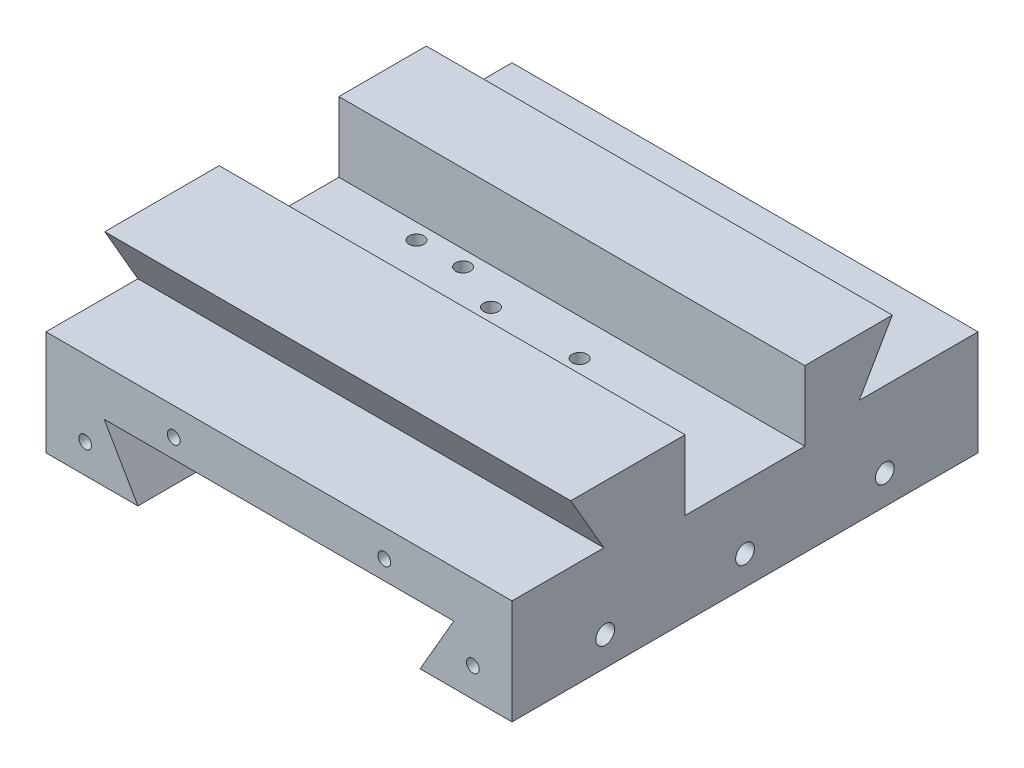
SolidWorks part; units mm, degrees
material "Ductile Iron"
ref_plane "Front Plane" through (0, 0, 0) normal (0, 0, 1) x (1, 0, 0)
ref_plane "Top Plane" through (0, 0, 0) normal (0, 1, 0) x (1, 0, 0)
ref_plane "Right Plane" through (0, 0, 0) normal (1, 0, 0) x (0, 0, -1)
sketch "Sketch10" plane through (0, 0, 0) normal (0, 0, 1) x (1, 0, 0)
  line B0 (-63.5, -15.875) -> (63.5, -15.875)
  line B1 (63.5, 0) -> (38.4596, 0)
  line B2 (38.4596, 0) -> (47.625, 15.875)
  line B3 (47.625, 15.875) -> (16.0563, 15.875)
  line B4 (-40.2927, 15.875) -> (-31.1272, 0)
  line B5 (-31.1272, 0) -> (-63.5, 0)
  line B6 (-63.5, 0) -> (-63.5, -15.875)
  line B7 (-38.4596, 0) -> (-47.625, 15.875)
  line B8 (-47.625, 15.875) -> (-40.2927, 15.875)
  line B9 (-16.0563, 15.875) -> (-16.0563, -3.175)
  line B10 (-16.0563, -3.175) -> (16.0563, -3.175)
  line B11 (16.0563, -3.175) -> (16.0563, 15.875)
  line B12 (-16.0563, 15.875) -> (-40.2927, 15.875)
  line B13 (-63.5, 0) -> (-63.5, 31.75)
  line B14 (-63.5, 31.75) -> (63.5, 31.75)
  line B15 (63.5, 31.75) -> (63.5, 0)
  line B16 (-16.0563, 15.875) -> (16.0563, 15.875)
  line B17 (0, 31.75) -> (0, -15.875) construction
  line B18 (-38.4596, 0) -> (38.4596, 0) construction
  line B19 (-28.702, 21.082) -> (28.702, 21.082) construction
  line B20 (-25.4, -8.001) -> (25.4, -8.001) construction
  line B21 (-25.4, -8.001) -> (-25.4, 7.9375) construction
  line B22 (25.4, -8.001) -> (25.4, 7.9375) construction
  line B23 (-52.832, 7.9375) -> (52.832, 7.9375) construction
  circle B24 centre (0, 6.35) radius 18.669 construction
  line B25 (40.2927, 15.875) -> (31.1272, 0)
  line B26 (31.1272, 0) -> (38.4596, 0)
sketch_block_instance "dovetail pair-1"
sketch_block "dovetail pair" parameters "D8"=37.338, "D1"=60, "D2"=127, "D3"=6.35, "D4"=15.875, "D5"=31.75, "D6"=95.25, "D7"=19.05, "D9"=60, "D10"=31.75, "D11"=50.8, "D12"=23.876, "D13"=7.874, "D14"=10.668, "D15"=34.798, "D16"=21.082, "D17"=7.9375
sketch "Sketch11"
sketch_block_instance "dovetail pair-3"
sketch "female-dovetail-profile" plane through (0, 0, 0) normal (0, 0, 1) x (1, 0, 0)
  line L0 (-47.625, 15.875) -> (-40.2927, 15.875) construction
  line L1 (-16.0563, 15.875) -> (-40.2927, 15.875) construction
  line L2 (-16.0563, 15.875) -> (16.0563, 15.875) construction
  line L3 (47.625, 15.875) -> (16.0563, 15.875) construction
  line L4 (-47.625, 15.875) -> (-40.2927, 15.875)
  line L5 (-16.0563, 15.875) -> (-40.2927, 15.875)
  line L6 (-16.0563, 15.875) -> (16.0563, 15.875)
  line L7 (47.625, 15.875) -> (16.0563, 15.875)
  line L8 (-38.4596, 0) -> (-47.625, 15.875) construction
  line L9 (-63.5, 0) -> (-63.5, 31.75) construction
  line L10 (63.5, 31.75) -> (63.5, 0) construction
  line L11 (63.5, 0) -> (38.4596, 0) construction
  line L12 (38.4596, 0) -> (47.625, 15.875) construction
  line L13 (-38.4596, 0) -> (-47.625, 15.875)
  line L14 (-63.5, 0) -> (-63.5, 31.75)
  line L15 (63.5, 31.75) -> (63.5, 0)
  line L16 (63.5, 0) -> (38.4596, 0)
  line L17 (38.4596, 0) -> (47.625, 15.875)
  line L18 (-38.4596, 0) -> (-63.5, 0)
  line L20 (63.5, 31.75) -> (63.5, 44.45)
  line L21 (63.5, 44.45) -> (-63.5, 44.45)
  line L22 (-63.5, 44.45) -> (-63.5, 31.75)
  dimension "D1" = 44.45
extrude "x-carriage-extrude" add sketch "female-dovetail-profile" along normal mid plane 127
sketch "male-dovetail-shoulder-profile" plane through (0, 0, 0) normal (1, 0, 0) x (0, 0, -1)
  line L0 (40.2927, 44.45) -> (31.1272, 28.575) construction
  line L1 (-40.2927, 44.45) -> (-31.1272, 28.575) construction
  line L2 (38.4596, 28.575) -> (47.625, 44.45) construction
  line L3 (63.5, 28.575) -> (38.4596, 28.575) construction
  line L4 (-38.4596, 28.575) -> (-47.625, 44.45) construction
  line L5 (-40.2927, 44.45) -> (-31.1272, 28.575) construction
  line L6 (38.4596, 28.575) -> (47.625, 44.45) construction
  line L7 (63.5, 28.575) -> (38.4596, 28.575)
  line L8 (-16.0563, 44.45) -> (-16.0563, 25.4) construction
  line L9 (-16.0563, 25.4) -> (16.0563, 25.4) construction
  line L10 (16.0563, 25.4) -> (16.0563, 44.45) construction
  line L11 (47.625, 44.45) -> (16.0563, 44.45) construction
  line L12 (-47.4784, 44.196) -> (-38.4596, 28.575)
  line L13 (-16.0563, 44.45) -> (-40.2927, 44.45) construction
  line L14 (-16.0563, 44.45) -> (-16.0563, 25.4) construction
  line L15 (-16.0563, 25.4) -> (16.0563, 25.4) construction
  line L16 (16.0563, 25.4) -> (16.0563, 44.45) construction
  line L17 (47.625, 44.45) -> (16.0563, 44.45) construction
  line L18 (-38.4596, 28.575) -> (-63.5, 28.575)
  line L19 (-16.0563, 44.45) -> (-40.2927, 44.45) construction
  line L20 (-47.4784, 44.196) -> (-16.3103, 44.196)
  line L21 (-16.3103, 44.196) -> (-16.3103, 25.146)
  line L22 (-16.3103, 25.146) -> (16.3103, 25.146)
  line L23 (16.3103, 25.146) -> (16.3103, 44.196)
  line L24 (16.3103, 44.196) -> (40.146, 44.196)
  line L25 (40.146, 44.196) -> (31.1272, 28.575)
  line L26 (-63.5, 28.575) -> (-63.5, 44.45)
  line L27 (-63.5, 44.45) -> (63.5, 44.45)
  line L28 (63.5, 44.45) -> (63.5, 28.575)
  line L29 (0, 60.325) -> (0, 12.7) construction
  line L30 (31.1272, 28.575) -> (38.4596, 28.575) construction
  line L31 (31.1272, 28.575) -> (38.4596, 28.575)
  point P16 (0, 25.146)
  dimension "D2" = 0.254
  dimension "D3" = 0.254
  dimension "D1" = 0.254
extrude "y-guide-cut-extrude" cut sketch "male-dovetail-shoulder-profile" against normal mid plane 127
hole_wizard "#8-32 Tapped Hole1" positions "Sketch4" profile "Sketch5" tap size "#8-32" standard "ANSI Inch"
sketch "Sketch4" plane through (0, -15.875, 63.5) normal (0, 0, 1) x (1, 0, 0)
  point P32 (-52.832, 23.8125)
  point P34 (-28.702, 36.957)
  point P36 (28.702, 36.957)
  point P38 (52.832, 23.8125)
cosmetic thread "Hole Thread12" parameters "D1"=8.382, "D2"=4.1656
sketch "Sketch5" plane through (-52.832, 7.9375, 63.5) normal (1, 0, 0) x (0, -1, 0)
  line L0 (0, 0) -> (0, 13.3822)
  line L1 (0, 13.3822) -> (1.7272, 12.3444)
  line L2 (1.7272, 12.3444) -> (1.7272, 0)
  line L3 (1.7272, 0) -> (0, 0)
  line L4 (0, 13.3822) -> (-1.7272, 12.3444) construction
  line L5 (0, -6.35) -> (0, 107.95) construction
  dimension "Tap Drill Dia." = 3.4544
  dimension "Tap Drill Depth" = 12.3444
  dimension "Drill Angle" = 118
cosmetic thread "Hole Thread20" parameters "D1"=8.382, "D2"=4.1656
cosmetic thread "Hole Thread21" parameters "D1"=8.382, "D2"=4.1656
cosmetic thread "Hole Thread22" parameters "D1"=8.382, "D2"=4.1656
hole_wizard "#8-32 Tapped Hole2" positions "Sketch6" profile "Sketch7" tap size "#8-32" standard "ANSI Inch"
sketch "Sketch6" plane through (0, -15.875, -63.5) normal (0, 0, -1) x (-1, 0, 0)
  point P8 (-52.832, 23.8125)
  point P10 (-28.702, 36.957)
  point P12 (28.702, 36.957)
  point P14 (52.832, 23.8125)
cosmetic thread "Hole Thread15" parameters "D1"=8.382, "D2"=4.1656
sketch "Sketch7" plane through (52.832, 7.9375, -63.5) normal (1, 0, 0) x (0, 1, 0)
  line L0 (0, 0) -> (0, 13.4838)
  line L1 (0, 13.4838) -> (1.7272, 12.446)
  line L2 (1.7272, 12.446) -> (1.7272, 0)
  line L5 (1.7272, 0) -> (0, 0)
  line L10 (0, 13.4838) -> (-1.7272, 12.446) construction
  line L11 (0, -6.35) -> (0, 107.95) construction
  dimension "Tap Drill Dia." = 3.4544
  dimension "Tap Drill Depth" = 12.446
  dimension "Drill Angle" = 118
cosmetic thread "Hole Thread23" parameters "D1"=8.382, "D2"=4.1656
cosmetic thread "Hole Thread24" parameters "D1"=8.382, "D2"=4.1656
cosmetic thread "Hole Thread25" parameters "D1"=8.382, "D2"=4.1656
hole_wizard "gib screw 1/4-20 Tapped Hole1" positions "Sketch9" profile "Sketch8" tap size "1/4-20" standard "ANSI Inch"
sketch "Sketch9" plane through (0, 0, 0) normal (1, 0, 0) x (0, 0, -1)
  line L2 (0, 15.875) -> (0, 0) construction
  line L4 (63.5, 7.9375) -> (-63.5, 7.9375) construction
  line L7 (-38.1, 7.9375) -> (0, 7.9375) construction
  line L8 (63.5, 0) -> (63.5, 28.575) construction
  line L9 (-63.5, 15.875) -> (63.5, 15.875) construction
  line L10 (-63.5, 15.875) -> (63.5, 15.875)
  point P0 (-38.1, 7.9375)
  point P16 (0, 7.9375)
  point P22 (0, 7.9375)
  point P23 (38.1, 7.9375)
  dimension "D1" = 38.1
  dimension "D2" = 3
sketch "Sketch8" plane through (0, 7.9375, 38.1) normal (0, 1, 0) x (0, 0, 1)
  line L0 (0, 0) -> (0, 63.5)
  line L1 (0, 63.5) -> (2.5527, 63.5)
  line L2 (2.5527, 63.5) -> (2.5527, 0)
  line L5 (2.5527, 0) -> (0, 0)
  line L11 (0, -6.35) -> (0, 107.95) construction
  dimension "Thru Tap Drill Dia." = 5.1054
  dimension "Thru Tap Drill Depth" = 63.5
cosmetic thread "Hole Thread36" parameters "D1"=23.2203, "D2"=6.35
cosmetic thread "Hole Thread37" parameters "D1"=23.2203, "D2"=6.35
cosmetic thread "Hole Thread38" parameters "D1"=23.2203, "D2"=6.35
hole_wizard "#10-32 Tapped Hole1" positions "Sketch13" profile "Sketch12" tap size "#10-32" standard "ANSI Inch"
sketch "Sketch13" plane through (0, 25.146, 0) normal (0, 1, 0) x (1, 0, 0)
  line L1 (-12.065, -6.35) -> (12.065, -6.35) construction
  line L2 (-12.065, -6.35) -> (-12.065, 6.35) construction
  line L3 (-12.065, 6.35) -> (12.065, 6.35) construction
  line L4 (12.065, -6.35) -> (12.065, 6.35) construction
  line L6 (-38.1, -12.065) -> (-25.4, -12.065) construction
  line L7 (-38.1, -12.065) -> (-38.1, 12.065) construction
  line L8 (-38.1, 12.065) -> (-25.4, 12.065) construction
  line L9 (-25.4, -12.065) -> (-25.4, 12.065) construction
  line L10 (0, 16.3103) -> (0, -16.3103) construction
  line L12 (-63.5, -16.3103) -> (63.5, -16.3103) construction
  line L13 (-63.5, 0) -> (63.5, 0) construction
  line L14 (-63.5, -16.3103) -> (-63.5, 16.3103) construction
  line L15 (63.5, -16.3103) -> (63.5, 16.3103) construction
  line L16 (-63.5, 16.3103) -> (63.5, 16.3103) construction
  point P0 (-38.1, 12.065)
  point P2 (-38.1, -12.065)
  point P4 (-12.065, 6.35)
  point P6 (-25.4, 12.065)
  point P8 (-25.4, -12.065)
  point P10 (12.065, 6.35)
  point P12 (12.065, -6.35)
  point P14 (-12.065, -6.35)
  point P155 (0, 0)
  point P157 (0, -6.35)
  point P158 (12.065, 0)
  point P159 (-25.4, 0)
  dimension "D1" = 24.13
  dimension "D2" = 24.13
  dimension "D3" = 12.7
  dimension "D4" = 12.7
  dimension "D5" = 38.1
sketch "Sketch12" plane through (-38.1, 25.146, -12.065) normal (1, 0, 0) x (0, 0, 1)
  line L0 (0, 0) -> (0, 9.271)
  line L1 (0, 9.271) -> (2.0193, 9.271)
  line L2 (2.0193, 9.271) -> (2.0193, 0)
  line L5 (2.0193, 0) -> (0, 0)
  line L11 (0, -6.35) -> (0, 107.95) construction
  dimension "Thru Tap Drill Dia." = 4.0386
  dimension "Thru Tap Drill Depth" = 9.271
cosmetic thread "Hole Thread28" parameters "D2"=4.826
cosmetic thread "Hole Thread29" parameters "D2"=4.826
cosmetic thread "Hole Thread30" parameters "D2"=4.826
cosmetic thread "Hole Thread31" parameters "D2"=4.826
cosmetic thread "Hole Thread32" parameters "D2"=4.826
cosmetic thread "Hole Thread33" parameters "D2"=4.826
cosmetic thread "Hole Thread34" parameters "D2"=4.826
cosmetic thread "Hole Thread35" parameters "D2"=4.826
equation "\"dovetail-angle\" = 60"
equation "\"dovetail-stock-width\" = 5"
equation "\"dovetail-stock-height\" = 1.25"
equation "\"dovetail-depth\" = 0.5 * \"dovetail-stock-height\""
equation "\"dovetail-throat-width\" = \"dovetail-stock-width\" - (2 * \"dovetail-depth\")"
equation "\"delta-x\" = 6"
equation "\"delta-y\" = 3"
equation "\"delta-z\"= 2.5"
equation "\"gib-thickness\" = 0.25"
equation "\"x-slide-length\" = \"dovetail-stock-width\" + \"delta-x\""
equation "\"y-slide-length\" = \"dovetail-stock-width\" + \"delta-y\""
equation "\"dog-point-diam\" = .149"
equation "\"D1@female-dovetail-profile\"=\"dovetail-double-height\""
equation "\"D1@x-carriage-extrude\"=\"dovetail-stock-width\""
equation "\"dog-point-length\" = .067"
equation "\"dovetail-double-height\" = 2 * \"dovetail-depth\" + 0.5"
equation "\"D2@male-dovetail-shoulder-profile\"=\"acme_nut_clearance\""
equation "\"D3@male-dovetail-shoulder-profile\"=\"dovetail_male_clearance\""
equation "\"acme-major-diam\" = .5"
equation "\"acme-pitch-diam\" = 0.45"
equation "\"acme-minor-diam\" = 0.4"
equation "\"acme-nut-od\" = 1.47"
equation "\"acme-nut-length\" = 1"
equation "\"acme-nut-trim-height\" = .75"
equation "\"screw-bearing-od\" = 0.5"
equation "\"screw-bearing-length\" = .375"
equation "\"screw-bearing-id\" = .375"
equation "\"end-plate-thickness\" = \"screw-bearing-length\""
equation "\"screw-add-length\" = 2 * \"end-plate-thickness\" + 1 + 0.5"
equation "\"x-screw-length\" = \"x-slide-length\" + \"screw-add-length\""
equation "\"y-screw-length\" = \"y-slide-length\" + \"screw-add-length\""
equation "\"acme-nut-mount-hole-space-horz\" = 0.95"
equation "\"acme-nut-mount-hole-space-vert\" = 0.5 * \"acme-nut-length\""
equation "\"D2@dovetail pair\"=\"dovetail-stock-width\""
equation "\"D1@dovetail pair\"=\"dovetail-angle\""
equation "\"D3@dovetail pair\"=\"gib-thickness\""
equation "\"D4@dovetail pair\"=\"dovetail-depth\""
equation "\"D5@dovetail pair\"=\"dovetail-stock-height\""
equation "\"D6@dovetail pair\"=\"dovetail-throat-width\""
equation "\"D10@dovetail pair\"=\"dovetail-stock-height\""
equation "\"D7@dovetail pair\"=\"acme-nut-trim-height\""
equation "\"D8@dovetail pair\"=\"acme-nut-od\""
equation "\"D9@dovetail pair\"=\"dovetail-angle\""
equation "\"D17@dovetail pair\"=\"dovetail-depth\"/2"
equation "\"acme-nut-trim-width\" = 1.25"
equation "\"vise-hole-center-dist\" = 6.75"
equation "\"wiper_plate_clearance\" = .03"
equation "\"dial-width\" = 0.5"
equation "\"quarter-twenty-free-fit\" = .2667"
equation "\"acme_nut_clearance\" = .01"
equation "\"dovetail_male_clearance\" = .01"
equation "\"D1@y-guide-cut-extrude\"=\"dovetail-stock-width\""
equation "\"D1@male-dovetail-shoulder-profile\"=\"acme_nut_clearance\""
equation "\"D1@Sketch13\"=\"acme-nut-mount-hole-space-horz\""
equation "\"D2@Sketch13\"=\"acme-nut-mount-hole-space-horz\""
equation "\"D3@Sketch13\"=\"acme-nut-mount-hole-space-vert\""
equation "\"D4@Sketch13\"=\"acme-nut-mount-hole-space-vert\""
